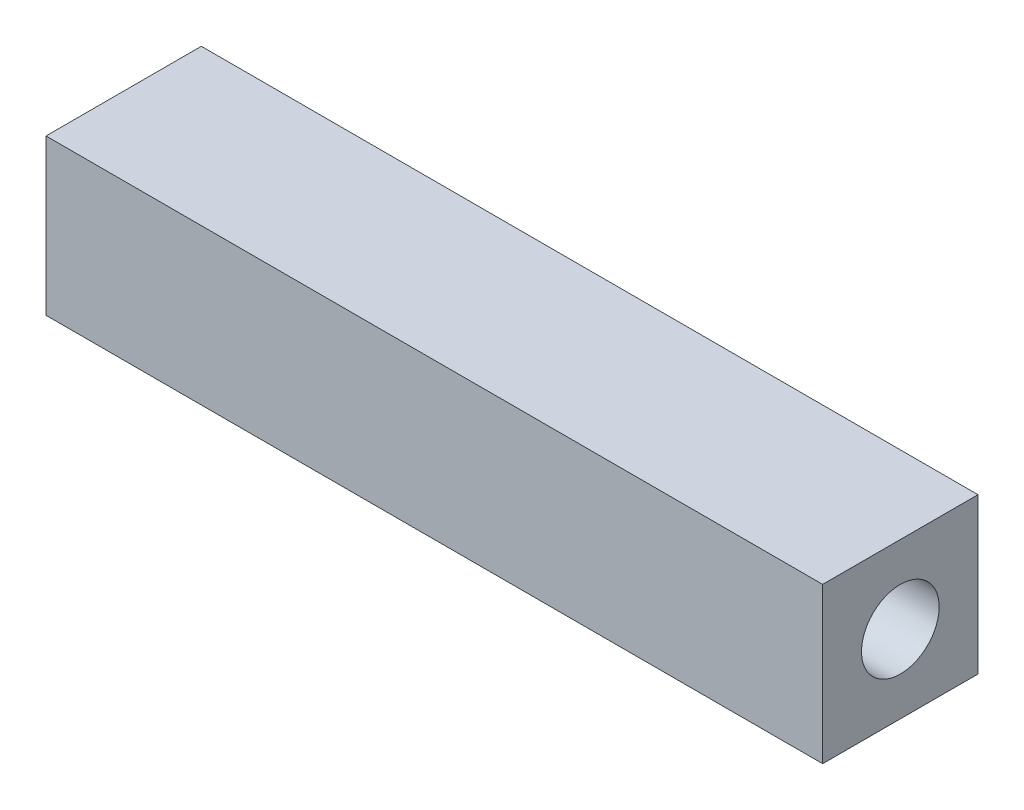
SolidWorks part; units mm, degrees
ref_plane "Alzado" through (0, 0, 0) normal (0, 0, 1) x (1, 0, 0)
ref_plane "Planta" through (0, 0, 0) normal (0, 1, 0) x (1, 0, 0)
ref_plane "Vista lateral" through (0, 0, 0) normal (1, 0, 0) x (0, 0, -1)
sketch "Croquis1" plane through (0, 0, 0) normal (1, 0, 0) x (0, 0, -1)
  line L1 (0, 0) -> (20, 0)
  line L2 (0, 0) -> (0, 20)
  line L3 (0, 20) -> (20, 20)
  line L4 (20, 0) -> (20, 20)
  circle A0 centre (10, 10) radius 5
  dimension "D3" = 10
  dimension "D1" = 20
  dimension "D2" = 20
extrude "Saliente-Extruir1" add sketch "Croquis1" along normal blind 100
